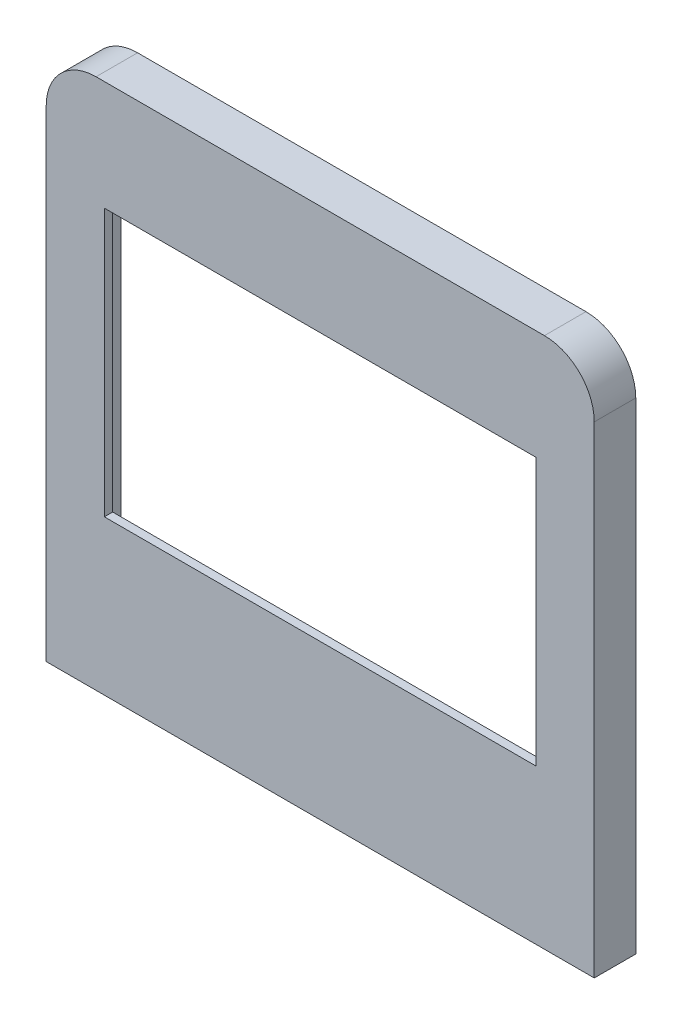
SolidWorks part; units mm, degrees
ref_plane "前视基准面" through (0, 0, 0) normal (0, 0, 1) x (1, 0, 0)
ref_plane "上视基准面" through (0, 0, 0) normal (0, 1, 0) x (1, 0, 0)
ref_plane "右视基准面" through (0, 0, 0) normal (1, 0, 0) x (0, 0, -1)
sketch "草图1" plane through (0, 0, 0) normal (0, 0, 1) x (1, 0, 0)
  line L0 (-16.165, 13.4373) -> (-16.165, -18.5627)
  line L1 (-14.165, 11.4373) -> (14.835, 11.4373) construction
  line L2 (-14.165, 11.4373) -> (-14.165, -16.5627) construction
  line L3 (-14.165, -16.5627) -> (14.835, -16.5627) construction
  line L4 (14.835, 11.4373) -> (14.835, -16.5627) construction
  line L5 (-16.165, -18.5627) -> (16.835, -18.5627)
  line L6 (16.835, 13.4373) -> (16.835, -18.5627)
  line L7 (-16.165, 13.4373) -> (16.835, 13.4373)
  line L8 (-12.665, 6.8373) -> (13.335, 6.8373)
  line L9 (-12.665, -9.2627) -> (13.335, -9.2627)
  line L10 (-12.665, 6.8373) -> (-12.665, -9.2627)
  line L11 (13.335, 6.8373) -> (13.335, -9.2627)
  dimension "D1" = 29
  dimension "D2" = 28
  dimension "D6" = 1.5
  dimension "D7" = 1.5
  dimension "D3" = 2
extrude "凸台-拉伸1" add sketch "草图1" along normal blind 0.5
ref_plane "基准面4" through (0, 0, 0) normal (0, 0, -1) x (-1, 0, 0)
sketch "草图2" plane through (0, 0, 0) normal (0, 0, -1) x (-1, 0, 0)
  line L0 (-16.835, -18.5627) -> (-16.835, 13.4373) construction
  line L1 (-16.835, 13.4373) -> (16.165, 13.4373)
  line L2 (-16.835, 13.4373) -> (-16.835, -18.5627)
  line L3 (-16.835, -18.5627) -> (16.165, -18.5627)
  line L4 (16.165, 13.4373) -> (16.165, -18.5627)
  line L5 (-16.835, 13.4373) -> (16.165, 13.4373) construction
  line L6 (-14.835, 11.4373) -> (-14.835, -16.5627)
  line L7 (-14.835, -16.5627) -> (14.165, -16.5627)
  line L8 (14.165, 11.4373) -> (14.165, -16.5627)
  line L9 (-14.835, 11.4373) -> (14.165, 11.4373)
  dimension "D1" = 2
extrude "凸台-拉伸2" add sketch "草图2" along normal blind 2
fillet "圆角1" radius 3 1 edges at (16.835, 13.4373, -0.75)
fillet "圆角2" radius 3 1 edges at (-16.165, 13.4373, -0.75)
